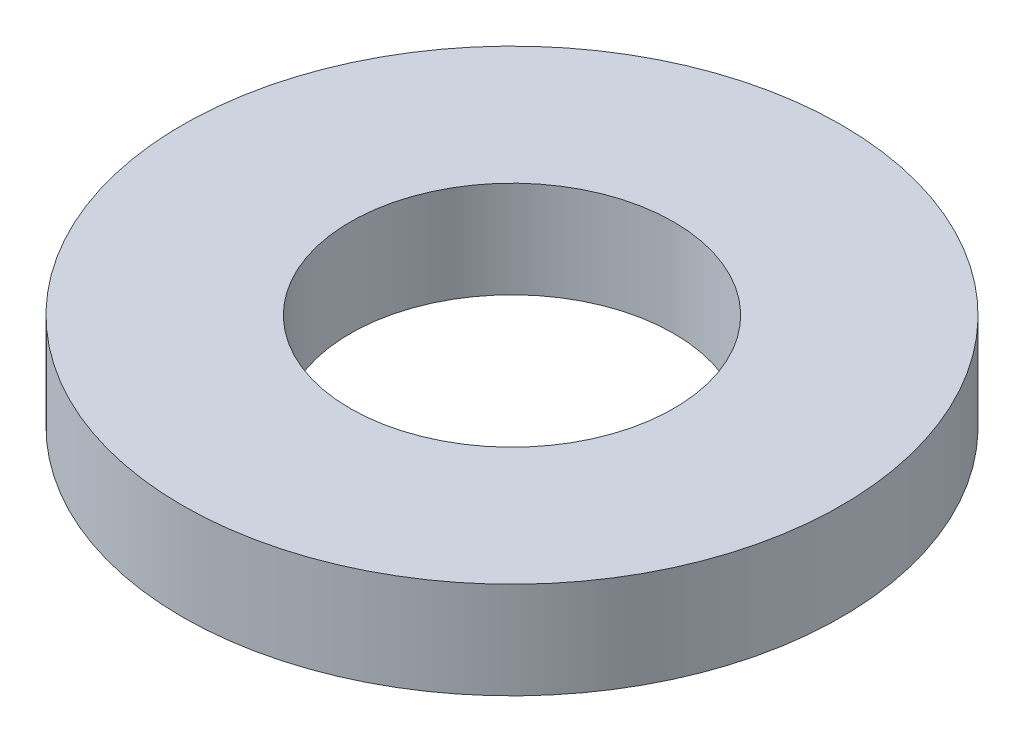
SolidWorks part; units mm, degrees
ref_plane "Front Plane" through (0, 0, 0) normal (0, 0, 1) x (1, 0, 0)
ref_plane "Top Plane" through (0, 0, 0) normal (0, 1, 0) x (1, 0, 0)
ref_plane "Right Plane" through (0, 0, 0) normal (1, 0, 0) x (0, 0, -1)
sketch "Sketch1" plane through (0, 0, 0) normal (0, 1, 0) x (1, 0, 0)
  circle A0 centre (0, 0) radius 4.7625
  dimension "OD" = 9.525
extrude "Boss-Extrude1" add sketch "Sketch1" along normal blind 1.397
sketch "Sketch5" plane through (0, 1.397, 0) normal (0, 1, 0) x (-1, 0, 0)
  circle A0 centre (0, 0) radius 2.3368
  dimension "ID" = 4.6736
extrude "Cut-Extrude1" cut sketch "Sketch5" against normal through all
